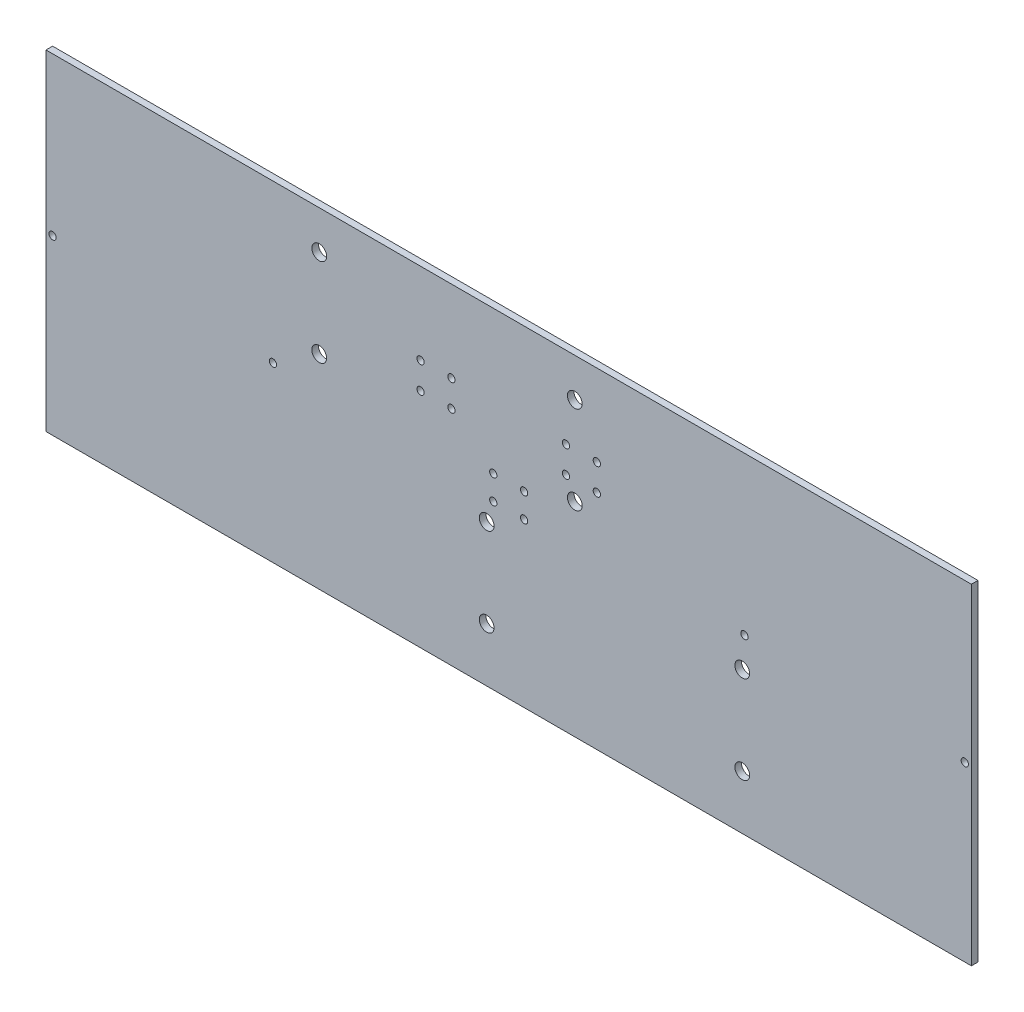
SolidWorks part; units mm, degrees
ref_plane "前视基准面" through (0, 0, 0) normal (0, 0, 1) x (1, 0, 0)
ref_plane "上视基准面" through (0, 0, 0) normal (0, 1, 0) x (1, 0, 0)
ref_plane "右视基准面" through (0, 0, 0) normal (1, 0, 0) x (0, 0, -1)
other "Configuration Table"
sketch "草图2" plane through (0, 0, 0) normal (0, 0, 1) x (1, 0, 0)
  line L1 (0, 0) -> (420, 0)
  line L2 (0, 0) -> (0, 180)
  line L3 (0, 180) -> (420, 180)
  line L4 (420, 0) -> (420, 180)
  dimension "D1" = 420
  dimension "D2" = 180
extrude "凸台-拉伸1" add sketch "草图2" along normal blind 3
sketch "草图3" plane through (0, 180, 0) normal (0, 1, 0) x (1, 0, 0)
  line L4 (420, 0) -> (0, 0)
  line L5 (0, 0) -> (0, -3)
  line L6 (0, -3) -> (420, -3)
  line L7 (420, -3) -> (420, 0)
  line L8 (420, 0) -> (0, 0)
  line L9 (0, 0) -> (0, -3)
  line L10 (0, -3) -> (420, -3)
  line L11 (420, -3) -> (420, 0)
  dimension "D1" = 0
extrude "切除-拉伸1" cut sketch "草图3" against normal blind 30
sketch "草图4" plane through (0, 0, 0) normal (0, 0, -1) x (-1, 0, 0)
  circle A0 centre (-250, 101) radius 1.65 construction
  circle A1 centre (-250, 113) radius 1.65 construction
  circle A2 centre (-236, 101) radius 1.65 construction
  circle A3 centre (-236, 113) radius 1.65 construction
  circle A4 centre (-250, 101) radius 1.65
  circle A5 centre (-250, 113) radius 1.65
  circle A6 centre (-236, 101) radius 1.65
  circle A7 centre (-236, 113) radius 1.65
  circle A8 centre (-200, 64.5) radius 3.25 construction
  circle A9 centre (-217, 85) radius 1.65
  circle A10 centre (-217, 85) radius 1.65
  circle A11 centre (-217, 74) radius 1.65
  circle A12 centre (-217, 74) radius 1.65
  circle A13 centre (-203, 85) radius 1.65
  circle A14 centre (-203, 85) radius 1.65
  circle A15 centre (-203, 74) radius 1.65
  circle A16 centre (-203, 74) radius 1.65
  circle A17 centre (-184, 113) radius 1.65
  circle A18 centre (-184, 113) radius 1.65
  circle A19 centre (-184, 101) radius 1.65
  circle A20 centre (-184, 101) radius 1.65
  circle A21 centre (-170, 101) radius 1.65
  circle A22 centre (-170, 101) radius 1.65
  circle A23 centre (-170, 113) radius 1.65
  circle A24 centre (-170, 113) radius 1.65
  circle A25 centre (-200, 24.5) radius 3.25 construction
  circle A26 centre (-200, 64.5) radius 3.25 construction
  circle A27 centre (-200, 24.5) radius 3.25 construction
  circle A28 centre (-316, 24.5) radius 3.25 construction
  circle A29 centre (-316, 24.5) radius 3.25 construction
  circle A30 centre (-316, 64.5) radius 3.25 construction
  circle A31 centre (-316, 64.5) radius 3.25 construction
  circle A32 centre (-240, 92.5) radius 3.25 construction
  circle A33 centre (-240, 132.5) radius 3.25 construction
  circle A34 centre (-240, 92.5) radius 3.25 construction
  circle A35 centre (-240, 132.5) radius 3.25 construction
  circle A36 centre (-124, 132.5) radius 3.25 construction
  circle A37 centre (-124, 92.5) radius 3.25 construction
  circle A38 centre (-124, 132.5) radius 3.25 construction
  circle A39 centre (-124, 92.5) radius 3.25 construction
  circle A40 centre (-317, 78.5) radius 1.5 construction
  circle A41 centre (-317, 78.5) radius 1.5 construction
  circle A42 centre (-417, 78.5) radius 1.5 construction
  circle A43 centre (-417, 78.5) radius 1.5 construction
  circle A44 centre (-3, 78.5) radius 1.5 construction
  circle A45 centre (-3, 78.5) radius 1.5 construction
  circle A46 centre (-103, 78.5) radius 1.5 construction
  circle A47 centre (-103, 78.5) radius 1.5 construction
  circle A48 centre (-417, 78.5) radius 1.65
  circle A49 centre (-317, 78.5) radius 1.65
  circle A50 centre (-3, 78.5) radius 1.65
  circle A51 centre (-103, 78.5) radius 1.65
  circle A52 centre (-316, 64.5) radius 3.35
  circle A53 centre (-316, 24.5) radius 3.35
  circle A54 centre (-200, 24.5) radius 3.35
  circle A55 centre (-200, 64.5) radius 3.35
  circle A56 centre (-240, 132.5) radius 3.35
  circle A57 centre (-240, 92.5) radius 3.35
  circle A58 centre (-124, 132.5) radius 3.35
  circle A59 centre (-124, 92.5) radius 3.35
  dimension "D9" = 3.3
  dimension "D10" = 6.7
  dimension "D1" = 0
  dimension "D2" = 0
  dimension "D3" = 0
  dimension "D4" = 0
  dimension "D5" = 0
  dimension "D6" = 0
  dimension "D7" = 0
  dimension "D8" = 0
extrude "切除-拉伸2" cut sketch "草图4" against normal blind 40
